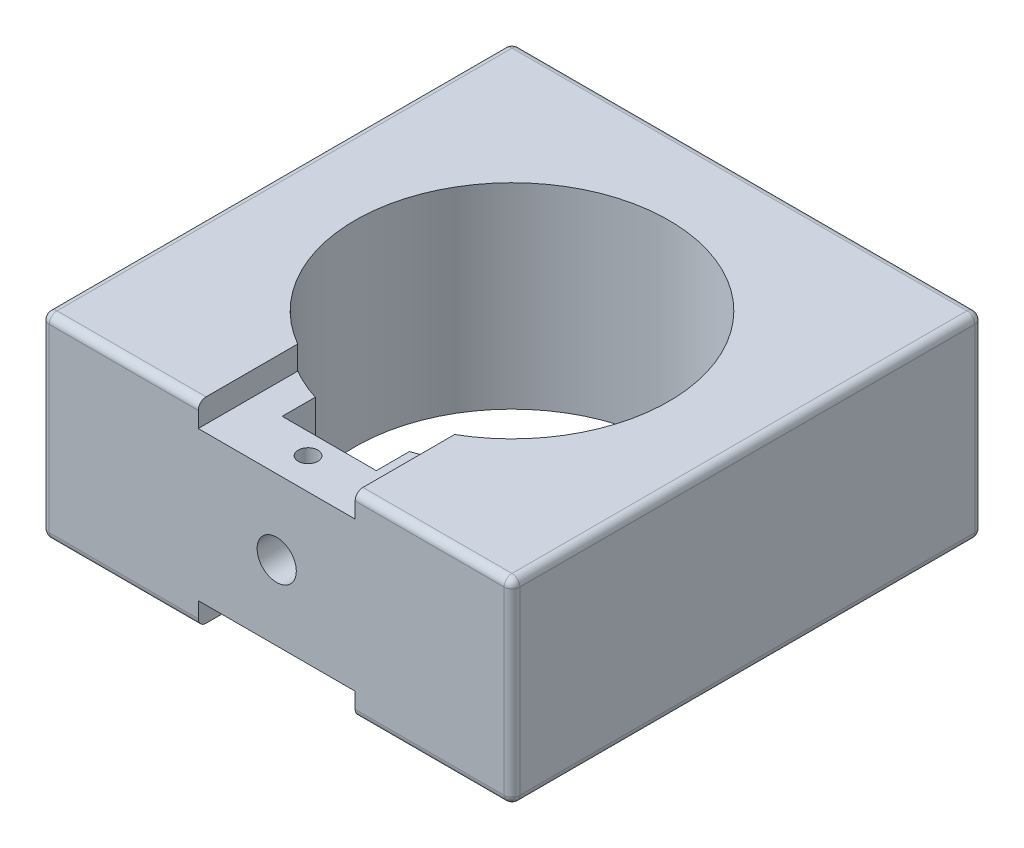
SolidWorks part; units mm, degrees
ref_plane "Plan de face" through (0, 0, 0) normal (0, 0, 1) x (1, 0, 0)
ref_plane "Plan de dessus" through (0, 0, 0) normal (0, 1, 0) x (1, 0, 0)
ref_plane "Plan de droite" through (0, 0, 0) normal (1, 0, 0) x (0, 0, -1)
sketch "Esquisse1" plane through (0, 0, 0) normal (0, 1, 0) x (1, 0, 0)
  line L7 (30, 30) -> (-30, 30)
  line L8 (30, 30) -> (30, -30)
  line L9 (30, -30) -> (-30, -30)
  line L10 (-30, 30) -> (-30, -30)
  line L11 (30, 30) -> (-30, -30) construction
  line L12 (30, -30) -> (-30, 30) construction
  circle A0 centre (0, 0) radius 20
  point P0 (0, 0)
  point P6 (0, 0)
  dimension "D2" = 40
  dimension "D1" = 60
extrude "Boss.-Extru.1" add sketch "Esquisse1" along normal blind 25
fillet "Congé1" radius 1 12 edges at (-30, 25, 0) (-30, 0, 0) (-30, 12.5, 30) (0, 25, 30) (0, 0, 30) (0, 25, -30) (-30, 12.5, -30) (0, 0, -30) (30, 12.5, 30) (30, 25, 0) (30, 12.5, -30) (30, 0, 0)
hole_wizard "Trou taraudé M61" positions "Esquisse4" profile "Esquisse5" tap size "M6" standard "DIN"
sketch "Esquisse4" plane through (0, 0, 30) normal (0, 0, 1) x (1, 0, 0)
  line L0 (0, 1) -> (0, 24) construction
  line L1 (-29, 1) -> (29, 1) construction
  line L2 (29, 24) -> (-29, 24) construction
  point P0 (0, 12.5)
sketch "Esquisse5" plane through (0, 12.5, 30) normal (1, 0, 0) x (0, -1, 0)
  line L0 (0, 0) -> (0, 10)
  line L1 (0, 10) -> (2.5, 10)
  line L2 (2.5, 10) -> (2.5, 0)
  line L5 (2.5, 0) -> (0, 0)
  line L11 (0, -6.35) -> (0, 107.95) construction
  dimension "Diamètre du trou pour taraudage jusqu'au prochain" = 5
  dimension "Profondeur du trou pour taraudage jusqu'au prochain" = 10
cosmetic thread "Filetage de perçage1" parameters "D2"=6
hole_wizard "Trou taraudé M41" positions "Esquisse6" profile "Esquisse7" tap size "M4" standard "DIN"
sketch "Esquisse6" plane through (0, 0, -30) normal (0, 0, -1) x (-1, 0, 0)
  line L0 (29, 12.5) -> (11.7, 12.5) construction
  line L1 (29, 1) -> (29, 24) construction
  line L2 (11.7, 12.5) -> (-11.7, 12.5) construction
  line L3 (-11.7, 12.5) -> (-29, 12.5) construction
  line L4 (-29, 24) -> (-29, 1) construction
  point P0 (11.7, 12.5)
  point P2 (-11.7, 12.5)
  dimension "D1" = 23.4
sketch "Esquisse7" plane through (-11.7, 12.5, -30) normal (1, 0, 0) x (0, 1, 0)
  line L0 (0, 0) -> (0, 8.4914)
  line L1 (0, 8.4914) -> (1.65, 7.5)
  line L2 (1.65, 7.5) -> (1.65, 0)
  line L5 (1.65, 0) -> (0, 0)
  line L10 (0, 8.4914) -> (-1.65, 7.5) construction
  line L11 (0, -6.35) -> (0, 107.95) construction
  dimension "Diamètre du trou pour taraudage" = 3.3
  dimension "Profondeur du trou pour taraudage" = 7.5
  dimension "Angle de pointe" = 118
cosmetic thread "Filetage de perçage2" parameters "D1"=4, "D2"=4
cosmetic thread "Filetage de perçage3" parameters "D1"=4, "D2"=4
hole_wizard "Trou taraudé M42" positions "Esquisse8" profile "Esquisse9" tap size "M4" standard "DIN"
sketch "Esquisse8" plane through (-30, 0, 0) normal (-1, 0, 0) x (0, 0, 1)
  line L3 (29, 12.5) -> (9.6667, 12.5) construction
  line L4 (29, 1) -> (29, 24) construction
  line L5 (9.6667, 12.5) -> (-9.6667, 12.5) construction
  line L6 (-9.6667, 12.5) -> (-29, 12.5) construction
  line L7 (-29, 24) -> (-29, 1) construction
  point P0 (-9.6667, 12.5)
sketch "Esquisse9" plane through (-30, 12.5, -9.6667) normal (0, 1, 0) x (0, 0, 1)
  line L0 (0, 0) -> (0, 11.4914)
  line L1 (0, 11.4914) -> (1.65, 10.5)
  line L2 (1.65, 10.5) -> (1.65, 0)
  line L5 (1.65, 0) -> (0, 0)
  line L10 (0, 11.4914) -> (-1.65, 10.5) construction
  line L11 (0, -6.35) -> (0, 107.95) construction
  dimension "Diamètre du trou pour taraudage" = 3.3
  dimension "Profondeur du trou pour taraudage" = 10.5
  dimension "Angle de pointe" = 118
cosmetic thread "Filetage de perçage6" parameters "D1"=7, "D2"=4
sketch "Esquisse10" plane through (0, 0, 0) normal (0, -1, 0) x (1, 0, 0)
  line L0 (-6, 19.0788) -> (-6, 23.3)
  line L1 (-6, 23.3) -> (6, 23.3)
  line L2 (6, 23.3) -> (6, 19.0788)
  line L3 (-6, 20) -> (6, 20) construction
  circle A0 centre (0, 0) radius 20 construction
  arc A1 (6, 19.0788) -> (-6, 19.0788) centre (0, 0) ccw
  dimension "D1" = 12
  dimension "D2" = 3.3
extrude "Enlèv. mat.-Extru.1" cut sketch "Esquisse10" against normal up to next
ref_plane "Plan1" through (0, 12.5, 0) normal (0, -1, 0) x (-1, 0, 0)
sketch "Esquisse11" plane through (0, 0, 0) normal (0, -1, 0) x (1, 0, 0)
  line L0 (-10, 30) -> (-10, 17.3205)
  line L1 (-29, 30) -> (29, 30) construction
  line L2 (10, 17.3205) -> (10, 30)
  line L3 (10, 30) -> (-10, 30)
  arc A0 (-6, 19.0788) -> (6, 19.0788) centre (0, 0) ccw construction
  arc A1 (-10, 17.3205) -> (10, 17.3205) centre (0, 0) cw
  arc A2 (-6, 19.0788) -> (6, 19.0788) centre (0, 0) ccw construction
  dimension "D1" = 20
extrude "Enlèv. mat.-Extru.2" cut sketch "Esquisse11" against normal blind 3
hole_wizard "Trou taraudé M31" positions "Esquisse12" profile "Esquisse13" tap size "M3" standard "DIN"
sketch "Esquisse12" plane through (0, 3, 0) normal (0, -1, 0) x (-1, 0, 0)
  line L0 (0, -23.3) -> (0, -30) construction
  line L1 (-6, -23.3) -> (6, -23.3) construction
  line L2 (-10, -30) -> (10, -30) construction
  point P4 (0, -26)
  dimension "D2" = 4
sketch "Esquisse13" plane through (0, 3, 26) normal (1, 0, 0) x (0, 0, -1)
  line L0 (0, 0) -> (0, 6.2511)
  line L1 (0, 6.2511) -> (1.25, 5.5)
  line L2 (1.25, 5.5) -> (1.25, 0)
  line L5 (1.25, 0) -> (0, 0)
  line L10 (0, 6.2511) -> (-1.25, 5.5) construction
  line L11 (0, -6.35) -> (0, 107.95) construction
  dimension "Diamètre du trou pour taraudage" = 2.5
  dimension "Profondeur du trou pour taraudage" = 5.5
  dimension "Angle de pointe" = 118
cosmetic thread "Filetage de perçage4" parameters "D1"=3, "D2"=3
mirror "Symétrie1" about plane through (0, 12.5, 0) normal (0, -1, 0) of "Trou taraudé M31", "Enlèv. mat.-Extru.2"
equation "\"d1\"= 10"
equation "\"d2\"= 2"
equation "\"d3\"= 30"
